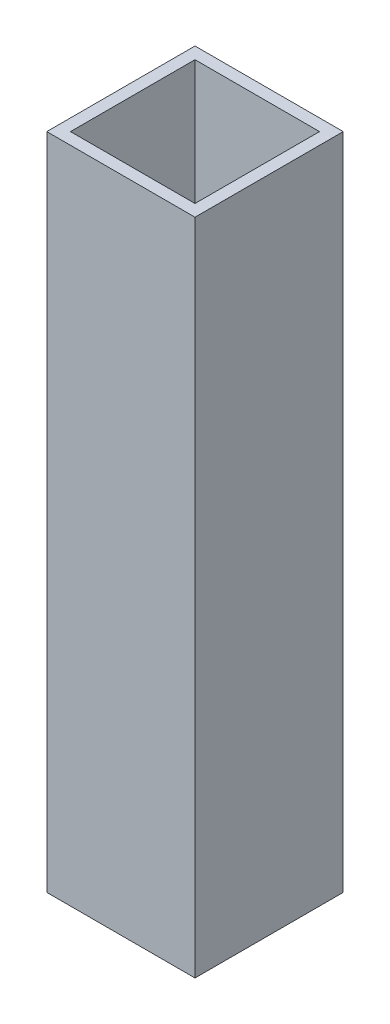
SolidWorks part; units mm, degrees
ref_plane "Front Plane" through (0, 0, 0) normal (0, 0, 1) x (1, 0, 0)
ref_plane "Top Plane" through (0, 0, 0) normal (0, 1, 0) x (1, 0, 0)
ref_plane "Right Plane" through (0, 0, 0) normal (1, 0, 0) x (0, 0, -1)
sketch "Sketch1" plane through (0, 0, 0) normal (0, 1, 0) x (1, 0, 0)
  line L1 (-18.9, -18.9) -> (18.9, -18.9)
  line L2 (-18.9, -18.9) -> (-18.9, 18.9)
  line L3 (-18.9, 18.9) -> (18.9, 18.9)
  line L4 (18.9, -18.9) -> (18.9, 18.9)
  line L5 (-18.9, -18.9) -> (18.9, 18.9) construction
  line L6 (-18.9, 18.9) -> (18.9, -18.9) construction
  line L7 (-22.5, -22.5) -> (22.5, -22.5)
  line L8 (-22.5, -22.5) -> (-22.5, 22.5)
  line L9 (-22.5, 22.5) -> (22.5, 22.5)
  line L10 (22.5, -22.5) -> (22.5, 22.5)
  line L11 (-22.5, -22.5) -> (22.5, 22.5) construction
  line L12 (-22.5, 22.5) -> (22.5, -22.5) construction
  point P0 (0, 0)
  point P6 (0, 0)
  point P11 (-58.7782, 51.6141)
  point P12 (0, 0)
  point P13 (0, 0)
  point P14 (0, 0)
  dimension "D1" = 37.8
  dimension "D2" = 45
  dimension "D3" = 45
  dimension "D4" = 37.8
extrude "Boss-Extrude1" add sketch "Sketch1" against normal blind 200 contours L9 L10 L7 L8
equation "\"D3@Sketch1\"=\"D2@Sketch1\""
equation "\"D4@Sketch1\"=\"D1@Sketch1\""
